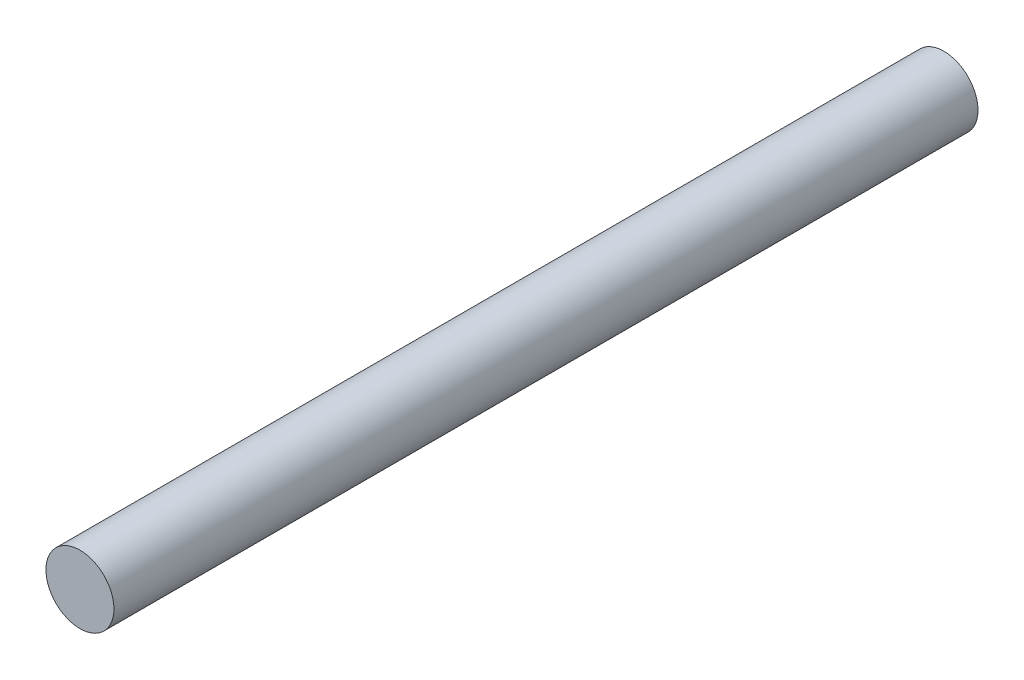
SolidWorks part; units mm, degrees
material "AISI 1020"
ref_plane "Front Plane" through (0, 0, 0) normal (0, 0, 1) x (1, 0, 0)
ref_plane "Top Plane" through (0, 0, 0) normal (0, 1, 0) x (1, 0, 0)
ref_plane "Right Plane" through (0, 0, 0) normal (1, 0, 0) x (0, 0, -1)
ref_plane "Plane1" through (0, 0, 25.4) normal (0, 0, 1) x (1, 0, 0)
ref_plane "Plane2" through (0, 0, 88.9) normal (0, 0, 1) x (1, 0, 0)
sketch "Sketch4" plane through (0, 0, 88.9) normal (0, 0, 1) x (1, 0, 0)
  circle A0 centre (0, 0) radius 4
  dimension "D1" = 8
extrude "Boss-Extrude1" add sketch "Sketch4" along normal blind 101.6
